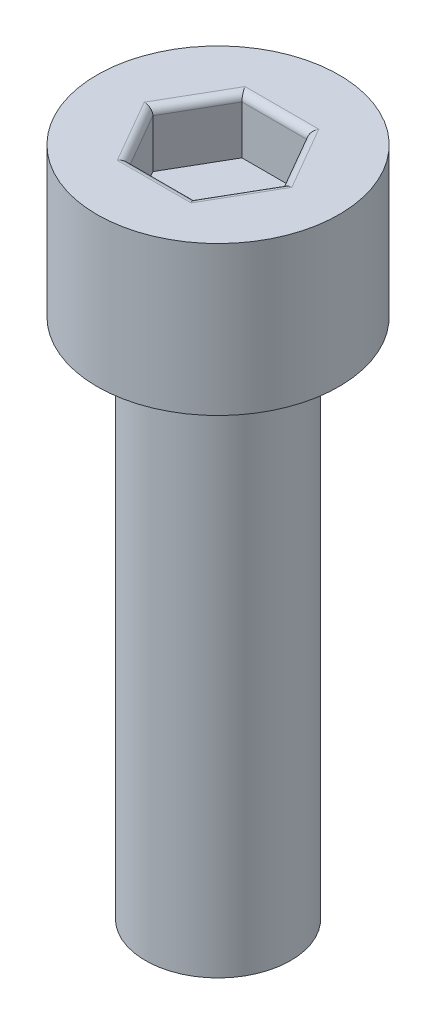
SolidWorks part; units mm, degrees
material "灰铸铁"
ref_plane "前视基准面" through (0, 0, 0) normal (0, 0, 1) x (1, 0, 0)
ref_plane "上视基准面" through (0, 0, 0) normal (0, 1, 0) x (1, 0, 0)
ref_plane "右视基准面" through (0, 0, 0) normal (1, 0, 0) x (0, 0, -1)
other "Configuration Table"
sketch "草图1" plane through (0, 0, 0) normal (0, 1, 0) x (1, 0, 0)
  circle A0 centre (0, 0) radius 3.25
  dimension "D1" = 6.5
extrude "凸台-拉伸1" add sketch "草图1" along normal blind 4
sketch "草图2" plane through (0, 4, 0) normal (0, 1, 0) x (1, 0, 0)
  line L0 (-0.875, 1.5155) -> (0.875, 1.5155)
  line L1 (0.875, 1.5155) -> (1.75, 0)
  line L2 (1.75, 0) -> (0.875, -1.5155)
  line L3 (0.875, -1.5155) -> (-0.875, -1.5155)
  line L4 (-0.875, -1.5155) -> (-1.75, 0)
  line L5 (-1.75, 0) -> (-0.875, 1.5155)
  line L6 (-0.875, 1.5155) -> (0.875, -1.5155) construction
  line L7 (-0.875, -1.5155) -> (0.875, 1.5155) construction
  point P2 (0, 0)
  point P8 (-0.9286, 1.6085)
  dimension "D1" = 120
  dimension "D2" = 120
  dimension "D3" = 3.5
  dimension "D4" = 3.5
extrude "切除-拉伸1" cut sketch "草图2" against normal blind 1.5 contours L5 L0 L1 L2 L3 L4
sketch "草图5" plane through (0, 0, 0) normal (0, -1, 0) x (1, 0, 0)
  circle A0 centre (0, 0) radius 1.95
  dimension "D1" = 3.9
extrude "凸台-拉伸2" add sketch "草图5" along normal blind 14
fillet "圆角1" radius 0.2 6 edges at (0, 4, -1.5155) (-1.3125, 4, -0.7578) (-1.3125, 4, 0.7578) (1.3125, 4, -0.7578) (0, 4, 1.5155) (1.3125, 4, 0.7578)
